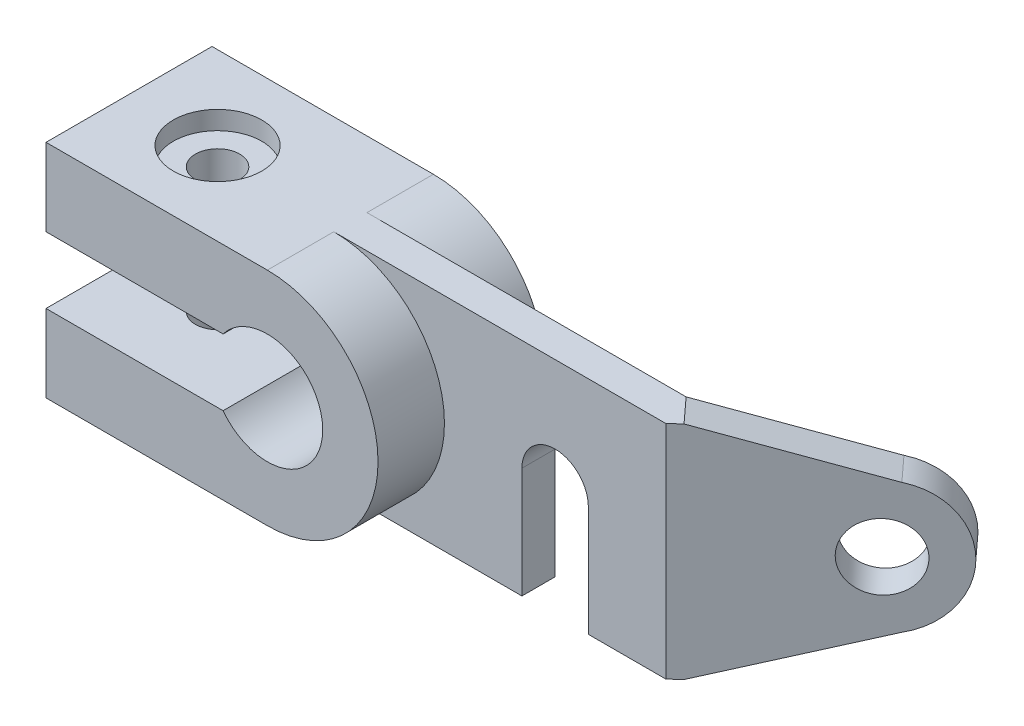
SolidWorks part; units mm, degrees
ref_plane "Front Plane" through (0, 0, 0) normal (0, 0, 1) x (1, 0, 0)
ref_plane "Top Plane" through (0, 0, 0) normal (0, 1, 0) x (1, 0, 0)
ref_plane "Right Plane" through (0, 0, 0) normal (1, 0, 0) x (0, 0, -1)
sketch "Sketch1" plane through (0, 0, 0) normal (0, 0, 1) x (1, 0, 0)
  line L0 (0, 30) -> (-60, 30)
  line L1 (0, -30) -> (-60, -30)
  line L2 (-60, -30) -> (-60, -9)
  line L4 (-55.1351, 9) -> (-60, 9) construction
  line L6 (-60, 9) -> (-12, 9)
  line L7 (-60, -9) -> (-12, -9)
  line L8 (-60, 9) -> (-60, 30)
  arc A0 (0, -30) -> (0, 30) centre (0, 0) ccw
  arc A1 (-12, -9) -> (-12, 9) centre (0, 0) ccw
  dimension "D1" = 60
  dimension "D3" = 30
  dimension "D2" = 60
extrude "Boss-Extrude1" add sketch "Sketch1" along normal blind 45
hole_wizard "CBORE for M10 Hex Head Bolt1" positions "Sketch4" profile "Sketch5" counterbore size "M10" standard "ANSI Metric"
sketch "Sketch4" plane through (0, 30, 0) normal (0, 1, 0) x (1, 0, 0)
  line L0 (-60, -45) -> (-60, 0) construction
  line L2 (0, 0) -> (-60, 0) construction
  point P0 (-36, -22.5)
  dimension "D1" = 24
  dimension "D2" = 22.5
sketch "Sketch5" plane through (-36, 30, 22.5) normal (1, 0, 0) x (0, 0, 1)
  line L0 (0, 0) -> (0, 24.6052)
  line L1 (0, 24.6052) -> (6, 21)
  line L2 (6, 21) -> (6, 5)
  line L3 (6, 5) -> (12, 5)
  line L4 (12, 5) -> (12, 0)
  line L5 (12, 0) -> (0, 0)
  line L10 (0, 24.6052) -> (-6, 21) construction
  line L11 (0, -6.35) -> (0, 107.95) construction
  dimension "Hole Dia." = 12
  dimension "Hole Depth" = 21
  dimension "C'Bore Dia." = 24
  dimension "C'Bore Depth" = 5
  dimension "Drill Angle" = 118
hole_wizard "CBORE for M10 Hex Head Bolt2" positions "Sketch6" profile "Sketch7" counterbore size "M10" standard "ANSI Metric"
sketch "Sketch6" plane through (0, -30, 0) normal (0, -1, 0) x (-1, 0, 0)
  line L0 (60, -45) -> (60, 0) construction
  line L1 (60, -45) -> (0, -45) construction
  point P0 (36, -22.5)
  dimension "D1" = 24
  dimension "D2" = 22.5
sketch "Sketch7" plane through (-36, -30, 22.5) normal (1, 0, 0) x (0, 0, -1)
  line L0 (0, 0) -> (0, 24.6042)
  line L1 (0, 24.6042) -> (6, 20.999)
  line L2 (6, 20.999) -> (6, 5)
  line L3 (6, 5) -> (12, 5)
  line L4 (12, 5) -> (12, 0)
  line L5 (12, 0) -> (0, 0)
  line L10 (0, 24.6042) -> (-6, 20.999) construction
  line L11 (0, -6.35) -> (0, 107.95) construction
  dimension "Hole Dia." = 12
  dimension "Hole Depth" = 20.999
  dimension "C'Bore Dia." = 24
  dimension "C'Bore Depth" = 5
  dimension "Drill Angle" = 118
sketch "Sketch8" plane through (-60, 0, 0) normal (-1, 0, 0) x (0, 0, 1)
  line L0 (45, 30) -> (0, 30) construction
  line L1 (18, 30) -> (27, 30)
  line L2 (18, 30) -> (18, -30)
  line L3 (18, -30) -> (27, -30)
  line L4 (27, 30) -> (27, -30)
  line L5 (45, -30) -> (0, -30) construction
  line L6 (45, 30) -> (45, 9) construction
  dimension "D1" = 9
  dimension "D2" = 18
extrude "Boss-Extrude5" add sketch "Sketch8" against normal blind 150
sketch "Sketch11" plane through (0, 30, 0) normal (0, 1, 0) x (1, 0, 0)
  circle A0 centre (-36, -22.5) radius 12
  point P4 (-36, -22.5)
extrude "Cut-Extrude3" cut sketch "Sketch11" against normal blind 5
sketch "Sketch13" plane through (0, 30, 0) normal (0, 1, 0) x (1, 0, 0)
  circle A0 centre (-36, -22.5) radius 6
extrude "Cut-Extrude4" cut sketch "Sketch13" against normal blind 99
sketch "Sketch14" plane through (0, -30, 0) normal (0, -1, 0) x (1, 0, 0)
  circle A0 centre (-36, 22.5) radius 12
extrude "Cut-Extrude5" cut sketch "Sketch14" against normal blind 5
sketch "Sketch15" plane through (0, 0, 27) normal (0, 0, 1) x (1, 0, 0)
  line L0 (-12, 9) -> (-60, 9)
  line L1 (-60, 9) -> (-60, -9)
  line L2 (-60, -9) -> (-12, -9)
  arc A0 (-12, -9) -> (-12, 9) centre (0, 0) ccw
extrude "Cut-Extrude6" cut sketch "Sketch15" against normal blind 68
sketch "Sketch16" plane through (0, 30, 0) normal (0, 1, 0) x (1, 0, 0)
  line L0 (90, -27) -> (134.637, 13.8386)
  line L1 (90, -27) -> (0, -27) construction
  line L2 (134.637, 13.8386) -> (128.5618, 20.4788)
  line L3 (83.9248, -20.3598) -> (128.5618, 20.4788)
  line L4 (90, -27) -> (83.9248, -20.3598)
  point P5 (127.8346, 21.2161)
  point P9 (126.2132, 22.976)
  point P12 (126.2275, 22.982)
  dimension "D1" = 137.544
  dimension "D2" = 60.5
  dimension "D3" = 90
  dimension "D4" = 9
extrude "Boss-Extrude8" add sketch "Sketch16" against normal up to surface (60 mm away) up to face at (-36, -30, 10.5)
sketch "Sketch17" plane through (48.3801, 0, 52.8799) normal (-0.675, 0, -0.7378) x (-0.7378, 0, 0.675)
  line L0 (-51.6725, -30) -> (-51.6725, 30) construction
  line L1 (-51.6725, -30) -> (-93.4694, -17.595)
  line L2 (-51.6725, 30) -> (-93.4694, 17.595)
  line L3 (-51.6725, 30) -> (-131.975, 46.2128)
  line L4 (-131.975, 46.2128) -> (-125.3354, -48.2024)
  line L5 (-125.3354, -48.2024) -> (-41.1452, -48.2024)
  line L6 (-41.1452, -48.2024) -> (-51.6725, -30)
  arc A1 (-93.4694, 17.595) -> (-93.4694, -17.595) centre (-89.6725, 0) ccw
  point P5 (-51.6725, 0)
  dimension "D2" = 36
  dimension "D3" = 0
  dimension "D4" = 38
extrude "Cut-Extrude7" cut sketch "Sketch17" against normal blind 68
sketch "Sketch18" plane through (48.3801, 0, 52.8799) normal (-0.675, 0, -0.7378) x (-0.7378, 0, 0.675)
  circle A0 centre (-89.6725, 0) radius 9
  dimension "D1" = 18
extrude "Cut-Extrude8" cut sketch "Sketch18" against normal blind 68
sketch "Sketch19" plane through (0, 0, 18) normal (0, 0, -1) x (-1, 0, 0)
  line L0 (-86.5041, 30) -> (0, 30) construction
  line L1 (-69, 0) -> (-69, -30)
  line L2 (-86.5041, -30) -> (0, -30) construction
  line L3 (-51, 0) -> (-51, -30)
  line L4 (-51, -30) -> (-69, -30)
  arc A0 (-51, 0) -> (-69, 0) centre (-60, 0) ccw
  dimension "D1" = 18
  dimension "D2" = 30
  dimension "D3" = 60
extrude "Cut-Extrude9" cut sketch "Sketch19" against normal blind 68
